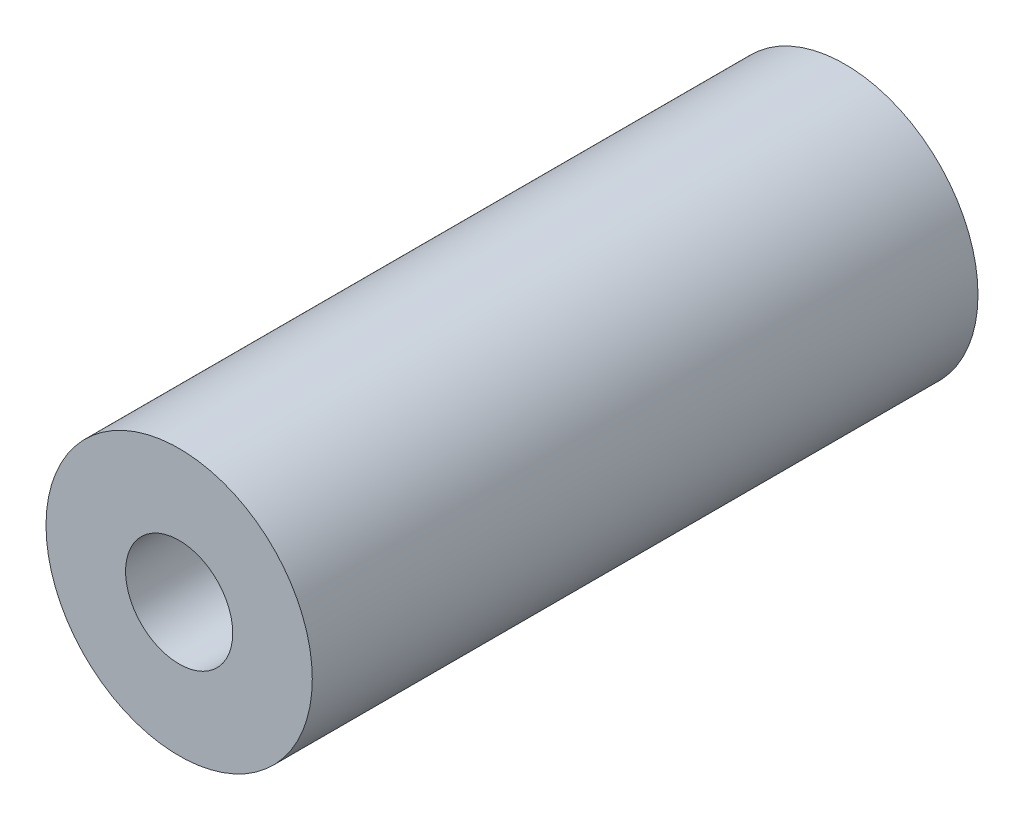
SolidWorks part; units mm, degrees
material "ABS"
ref_plane "Front Plane" through (0, 0, 0) normal (0, 0, 1) x (1, 0, 0)
ref_plane "Top Plane" through (0, 0, 0) normal (0, 1, 0) x (1, 0, 0)
ref_plane "Right Plane" through (0, 0, 0) normal (1, 0, 0) x (0, 0, -1)
sketch "Sketch1" plane through (0, 0, 0) normal (0, 0, 1) x (1, 0, 0)
  circle A0 centre (0, 0) radius 6.35
  circle A1 centre (0, 0) radius 2.555
  dimension "D1" = 12.7
  dimension "D2" = 5.11
extrude "Boss-Extrude1" add sketch "Sketch1" along normal blind 31.75
cosmetic thread "Cosmetic Thread1" parameters "D2"=6.35
